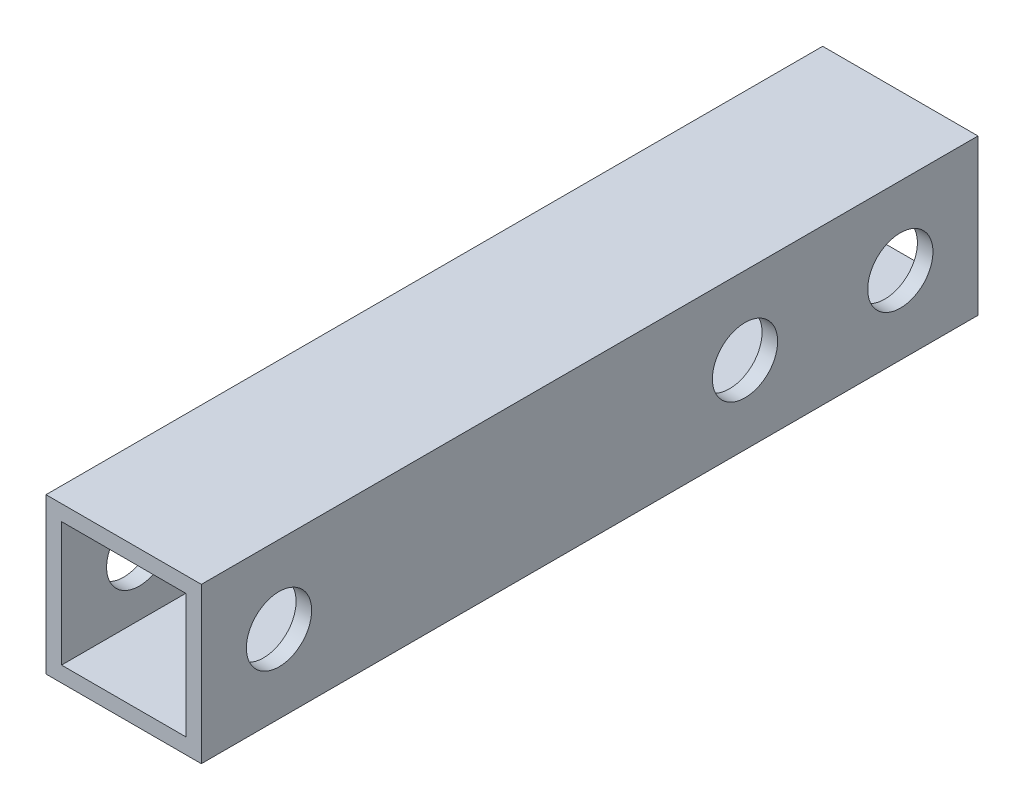
SolidWorks part; units mm, degrees
material "5052-H34"
ref_plane "正面" through (0, 0, 0) normal (0, 0, 1) x (1, 0, 0)
ref_plane "平面" through (0, 0, 0) normal (0, 1, 0) x (1, 0, 0)
ref_plane "右側面" through (0, 0, 0) normal (1, 0, 0) x (0, 0, -1)
sketch "ｽｹｯﾁ1" plane through (0, 0, 0) normal (0, 0, 1) x (1, 0, 0)
  line L1 (0, 0) -> (10, 0)
  line L2 (0, 0) -> (0, 10)
  line L3 (0, 10) -> (10, 10)
  line L4 (10, 0) -> (10, 10)
  dimension "D1" = 10
  dimension "D2" = 10
extrude "押し出し-薄板1" add sketch "ｽｹｯﾁ1" along normal blind 50 thin thin type one direction reverse wall 1
sketch "ｽｹｯﾁ2" plane through (10, 0, 0) normal (1, 0, 0) x (0, 0, -1)
  line L0 (0, 5) -> (-50, 5) construction
  line L1 (0, 0) -> (0, 10) construction
  line L2 (-50, 0) -> (-50, 10) construction
  circle A0 centre (-5, 5) radius 2.1
  circle A1 centre (-15, 5) radius 2.1
  circle A2 centre (-45, 5) radius 2.1
  dimension "D1" = 4.2
  dimension "D2" = 5
  dimension "D3" = 10
  dimension "D4" = 5
extrude "ｶｯﾄ - 押し出し1" cut sketch "ｽｹｯﾁ2" against normal up to surface (10 mm away) up to face at (0, 5, 25)
